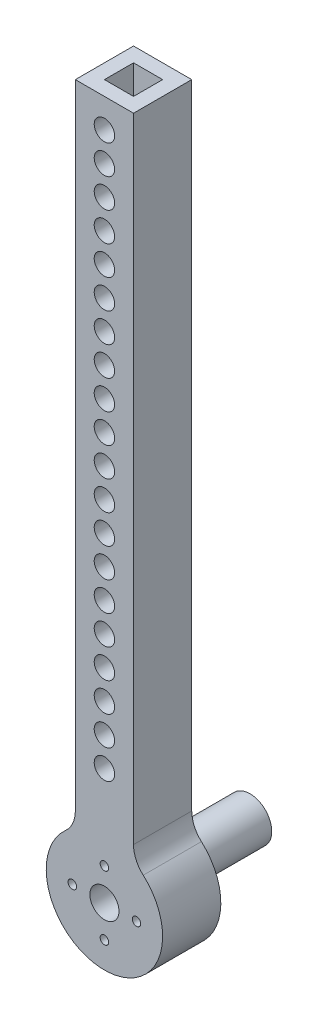
SolidWorks part; units mm, degrees
ref_plane "Front Plane" through (0, 0, 0) normal (0, 0, 1) x (1, 0, 0)
ref_plane "Top Plane" through (0, 0, 0) normal (0, 1, 0) x (1, 0, 0)
ref_plane "Right Plane" through (0, 0, 0) normal (1, 0, 0) x (0, 0, -1)
sketch "Sketch1" plane through (0, 0, 0) normal (0, 1, 0) x (1, 0, 0)
  line L0 (-3.175, -3.175) -> (-3.175, 3.175)
  line L1 (-6.35, -6.35) -> (6.35, -6.35)
  line L2 (-6.35, -6.35) -> (-6.35, 6.35)
  line L3 (-6.35, 6.35) -> (6.35, 6.35)
  line L4 (6.35, -6.35) -> (6.35, 6.35)
  line L5 (-6.35, -6.35) -> (6.35, 6.35) construction
  line L6 (-6.35, 6.35) -> (6.35, -6.35) construction
  line L7 (-3.175, 3.175) -> (3.175, 3.175)
  line L8 (3.175, -3.175) -> (3.175, 3.175)
  line L9 (-3.175, -3.175) -> (3.175, -3.175)
  point P0 (0, 0)
  dimension "D1" = 12.7
  dimension "D2" = 3.175
extrude "Boss-Extrude1" add sketch "Sketch1" along normal blind 152.4
sketch "Sketch2" plane through (0, 0, 6.35) normal (0, 0, 1) x (1, 0, 0)
  line L0 (-6.35, 0) -> (6.35, 0) construction
  circle A0 centre (0, 25.4) radius 2.227
  circle A10 centre (0, 31.75) radius 2.227
  circle A11 centre (0, 38.1) radius 2.227
  circle A12 centre (0, 44.45) radius 2.227
  circle A13 centre (0, 50.8) radius 2.227
  circle A14 centre (0, 57.15) radius 2.227
  circle A15 centre (0, 63.5) radius 2.227
  circle A16 centre (0, 69.85) radius 2.227
  circle A17 centre (0, 76.2) radius 2.227
  circle A18 centre (0, 82.55) radius 2.227
  circle A19 centre (0, 88.9) radius 2.227
  circle A20 centre (0, 95.25) radius 2.227
  circle A21 centre (0, 101.6) radius 2.227
  circle A22 centre (0, 107.95) radius 2.227
  circle A23 centre (0, 114.3) radius 2.227
  circle A24 centre (0, 120.65) radius 2.227
  circle A25 centre (0, 127) radius 2.227
  circle A26 centre (0, 133.35) radius 2.227
  circle A27 centre (0, 139.7) radius 2.227
  circle A28 centre (0, 146.05) radius 2.227
  dimension "D2" = 4.454
  dimension "D1" = 25.4
  dimension "D3" = 20
extrude "Cut-Extrude1" cut sketch "Sketch2" against normal through all
sketch "Sketch3" plane through (0, 0, 6.35) normal (0, 0, 1) x (1, 0, 0)
  circle A0 centre (0, 0) radius 12.7
  dimension "D1" = 25.4
extrude "Boss-Extrude2" add sketch "Sketch3" against normal blind 12.7
sketch "Sketch4" plane through (0, 0, 6.35) normal (0, 0, 1) x (1, 0, 0)
  circle A0 centre (0, 0) radius 4.7625
  dimension "D1" = 9.525
extrude "Boss-Extrude3" add sketch "Sketch4" against normal blind 31.75
sketch "Sketch6" plane through (0, 0, 6.35) normal (0, 0, 1) x (1, 0, 0)
  circle A0 centre (0, 0) radius 3.175
  circle A1 centre (7, 0) radius 0.927
  circle A2 centre (0, -7) radius 0.927
  circle A3 centre (-7, 0) radius 0.927
  circle A4 centre (0, 7) radius 0.927
  point P5 (-8.3369, -1.8015)
  point P6 (0, 0)
  point P14 (0, 0)
  dimension "D1" = 6.35
  dimension "D2" = 1.854
  dimension "D3" = 7
  dimension "D4" = 4
extrude "Cut-Extrude3" cut sketch "Sketch6" against normal through all
fillet "Fillet2" radius 6.35 2 edges at (-6.35, 10.9985, 0) (6.35, 10.9985, 0)
equation "\"tightTol\"= 0.005in"
equation "\"normTol\"= 0.01in"
equation "\"looseTol\"= 0.02in"
equation "\"Fry height\"= 0.5in"
equation "\"Fry spacing\"= 0.5625in"
equation "\"Potato width\"= \"Fry spacing\" * 4"
equation "\"Potato length\"= 3.5in"
equation "\"D2@Sketch6\"=1.6mm+\"normTol\""
equation "\"D3@Sketch6\"=7mm"
